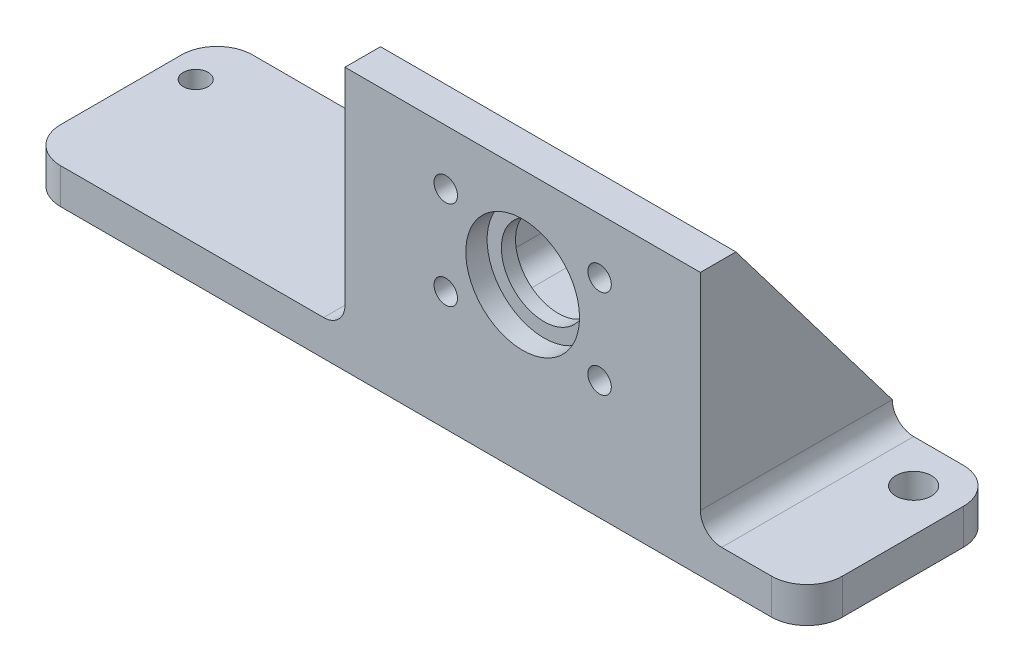
SolidWorks part; units mm, degrees
ref_plane "前视基准面" through (0, 0, 0) normal (0, 0, 1) x (1, 0, 0)
ref_plane "上视基准面" through (0, 0, 0) normal (0, 1, 0) x (1, 0, 0)
ref_plane "右视基准面" through (0, 0, 0) normal (1, 0, 0) x (0, 0, -1)
sketch "草图2" plane through (0, 0, 0) normal (0, 1, 0) x (1, 0, 0)
  line L0 (-70, 27) -> (-70, 10)
  line L1 (40, 27) -> (40, 10)
  line L3 (-65, 32) -> (35, 32)
  line L5 (-65, 5) -> (35, 5)
  arc A0 (-65, 32) -> (-70, 27) centre (-65, 27) ccw
  arc A1 (-65, 5) -> (-70, 10) centre (-65, 10) cw
  arc A2 (35, 5) -> (40, 10) centre (35, 10) ccw
  arc A3 (40, 27) -> (35, 32) centre (35, 27) ccw
  point P0 (0, 0)
  dimension "D1" = 5
extrude "凸台-拉伸1" add sketch "草图2" along normal blind 5
sketch "草图3" plane through (0, 5, 0) normal (0, 1, 0) x (1, 0, 0)
  circle A0 centre (-34, 26) radius 2.5
  circle A1 centre (34, 26) radius 2.5
  circle A2 centre (-66, 25) radius 1.75
  dimension "D1" = 5
  dimension "D2" = 3.5
extrude "切除-拉伸2" cut sketch "草图3" against normal through all
sketch "草图6" plane through (0, 5, 0) normal (0, 1, 0) x (1, 0, 0)
  line L0 (-25, 5) -> (-25, 32)
  line L1 (35, 32) -> (-65, 32) construction
  line L2 (-25, 32) -> (-19.9862, 32)
  line L3 (-25, 5) -> (25, 5)
  line L4 (25, 5) -> (25, 32)
  line L5 (-19.9862, 32) -> (-19.9862, 10)
  line L6 (25, 32) -> (19.3831, 32)
  line L7 (19.3831, 32) -> (19.3831, 10)
  line L8 (19.3831, 10) -> (-19.9862, 10)
extrude "凸台-拉伸2" add sketch "草图6" along normal blind 32
sketch "草图11" plane through (0, 0, -5) normal (0, 0, 1) x (1, 0, 0)
  circle A0 centre (-0.0009, 23) radius 18 construction
  circle A2 centre (-10.82, 29.25) radius 1.65
  circle A3 centre (10.82, 29.25) radius 1.65
  circle A4 centre (-10.82, 16.75) radius 1.65
  circle A5 centre (10.82, 16.75) radius 1.65
  dimension "D3" = 3.3
extrude "切除-拉伸3" cut sketch "草图11" against normal through all
hole_wizard "M5 六角头螺钉的柱形沉头孔1" positions "3D草图2" profile "草图17" counterbore size "M5" standard "ANSI Metric" end condition through all
sketch3d "3D草图2"
  point P0 (-0.0009, 23, -5)
sketch "草图17" plane through (-0.0009, 23, -5) normal (1, 0, 0) x (0, -1, 0)
  line L0 (0, 0) -> (0, 27.0001)
  line L1 (0, 27.0001) -> (6, 27.0001)
  line L3 (6, 27.0001) -> (6, 3)
  line L4 (6, 3) -> (8, 3)
  line L5 (8, 3) -> (8, 0)
  line L7 (8, 0) -> (0, 0)
  line L11 (0, -6.35) -> (0, 107.95) construction
  dimension "通孔孔直径" = 12
  dimension "通孔孔深度" = 27.0001
  dimension "柱形沉头孔直径" = 16
  dimension "柱形沉头孔深度" = 3
fillet "圆角2" radius 3 7 edges at (19.3831, 21, -10) (-19.9862, 21, -10) (-0.3015, 5, -10)
sketch "草图18" plane through (-25, 0, 0) normal (-1, 0, 0) x (0, 0, 1)
  line L0 (-10, 37) -> (-32, 8)
  line L1 (-32, 8) -> (-32, 37)
  line L2 (-32, 37) -> (-10, 37)
extrude "切除-拉伸4" cut sketch "草图18" against normal through all
